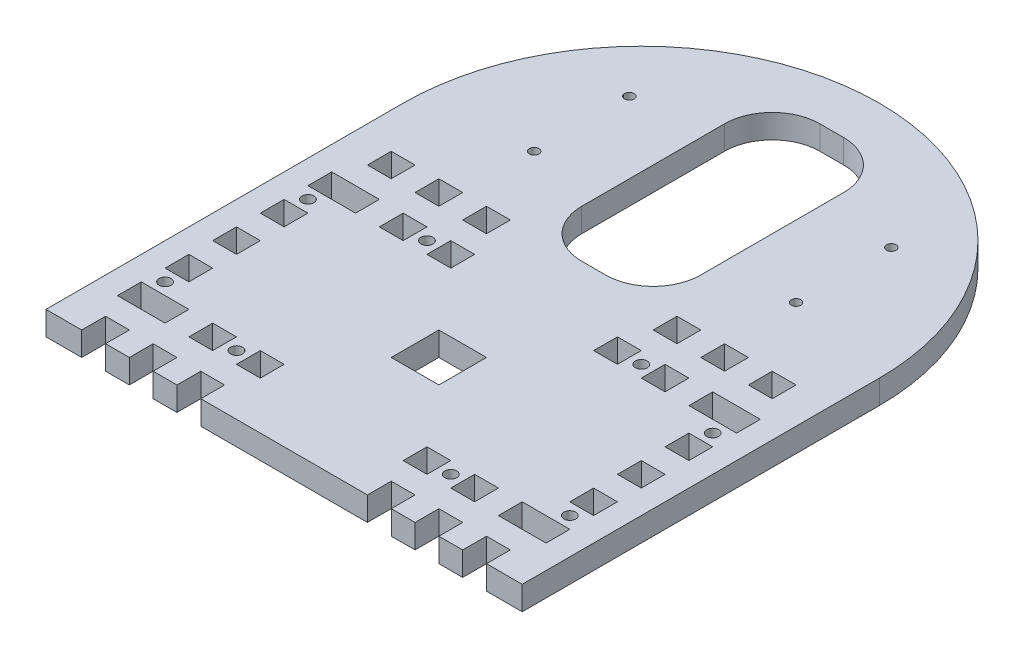
SolidWorks part; units mm, degrees
material "Acrylic (Medium-high impact)"
ref_plane "Front Plane" through (0, 0, 0) normal (0, 0, 1) x (1, 0, 0)
ref_plane "Top Plane" through (0, 0, 0) normal (0, 1, 0) x (1, 0, 0)
ref_plane "Right Plane" through (0, 0, 0) normal (1, 0, 0) x (0, 0, -1)
sketch "Sketch3" plane through (0, 0, 0) normal (0, 1, 0) x (1, 0, 0)
  line L1 (-100, -75) -> (100, -75)
  line L2 (-100, -75) -> (-100, 75)
  line L4 (100, -75) -> (100, 75)
  line L5 (-100, -75) -> (100, 75) construction
  line L6 (-100, 75) -> (100, -75) construction
  arc A0 (-100, 75) -> (100, 75) centre (0, 75) cw
  point P0 (0, 0)
  dimension "D1" = 200
  dimension "D2" = 150
extrude "Boss-Extrude1" add sketch "Sketch3" along normal blind 10
sketch "Sketch2" plane through (0, 10, 0) normal (0, 1, 0) x (1, 0, 0)
  line L1 (-100, -75) -> (100, -75) construction
  line L2 (100, -75) -> (100, 75) construction
  line L7 (30, -45) -> (40, -45)
  line L8 (30, -45) -> (30, -55)
  line L9 (30, -55) -> (40, -55)
  line L10 (40, -45) -> (40, -55)
  line L11 (50, -45) -> (60, -45)
  line L12 (50, -45) -> (50, -55)
  line L13 (50, -55) -> (60, -55)
  line L14 (60, -45) -> (60, -55)
  line L15 (70, -45) -> (90, -45)
  line L16 (70, -45) -> (70, -55)
  line L17 (70, -55) -> (90, -55)
  line L18 (90, -45) -> (90, -55)
  line L19 (90, -35) -> (80, -35)
  line L20 (90, -35) -> (90, -25)
  line L21 (90, -25) -> (80, -25)
  line L22 (80, -35) -> (80, -25)
  line L23 (90, -15) -> (80, -15)
  line L24 (90, -15) -> (90, -5)
  line L25 (90, -5) -> (80, -5)
  line L26 (80, -15) -> (80, -5)
  line L27 (90, 15) -> (80, 15)
  line L28 (90, 15) -> (90, 5)
  line L29 (90, 5) -> (80, 5)
  line L30 (80, 15) -> (80, 5)
  line L31 (90, 35) -> (70, 35)
  line L32 (90, 35) -> (90, 25)
  line L33 (90, 25) -> (70, 25)
  line L34 (70, 35) -> (70, 25)
  line L35 (60, 35) -> (50, 35)
  line L36 (60, 35) -> (60, 25)
  line L37 (60, 25) -> (50, 25)
  line L38 (50, 35) -> (50, 25)
  line L39 (40, 35) -> (30, 35)
  line L40 (40, 35) -> (40, 25)
  line L41 (40, 25) -> (30, 25)
  line L42 (30, 35) -> (30, 25)
  circle A0 centre (45, 30) radius 2.5
  circle A1 centre (45, -50) radius 2.5
  circle A2 centre (85, -40) radius 2.5
  circle A3 centre (85, 20) radius 2.5
  point P0 (0, 0)
  dimension "D3" = 10
  dimension "D19" = 5
  dimension "D23" = 5
  dimension "D2" = 20
  dimension "D4" = 10
  dimension "D5" = 10
  dimension "D6" = 10
  dimension "D7" = 10
  dimension "D8" = 20
  dimension "D9" = 10
  dimension "D10" = 10
  dimension "D11" = 10
  dimension "D12" = 10
  dimension "D13" = 10
  dimension "D14" = 10
  dimension "D15" = 10
  dimension "D16" = 10
  dimension "D17" = 10
  dimension "D18" = 10
  dimension "D20" = 5
  dimension "D21" = 5
  dimension "D22" = 5
  dimension "D24" = 5
  dimension "D25" = 5
extrude "Cut-Extrude1" cut sketch "Sketch2" against normal through all
mirror "Mirror1" about plane through (0, 0, 0) normal (1, 0, 0) of "Cut-Extrude1"
sketch "Sketch4" plane through (0, 10, 0) normal (0, 1, 0) x (1, 0, 0)
  line L0 (100, -75) -> (100, 75) construction
  line L1 (-100, -75) -> (100, -75) construction
  line L2 (-100, 75) -> (-100, -75) construction
  line L4 (-5, 155) -> (5, 155)
  line L5 (-25, 135) -> (-25, 75)
  line L6 (-5, 55) -> (5, 55)
  line L7 (25, 135) -> (25, 75)
  circle A0 centre (55, 125) radius 2
  circle A1 centre (55, 85) radius 2
  circle A2 centre (-55, 125) radius 2
  circle A3 centre (-55, 85) radius 2
  arc A4 (-5, 55) -> (-25, 75) centre (-5, 75) cw
  arc A5 (5, 55) -> (25, 75) centre (5, 75) ccw
  arc A6 (25, 135) -> (5, 155) centre (5, 135) ccw
  arc A7 (-5, 155) -> (-25, 135) centre (-5, 135) ccw
  point P18 (25, 105)
  point P24 (25, 55)
  point P27 (25, 155)
  point P30 (-25, 155)
  dimension "D1" = 4
  dimension "D2" = 4
  dimension "D3" = 4
  dimension "D4" = 4
  dimension "D16" = 20
  dimension "D5" = 110
  dimension "D6" = 110
  dimension "D7" = 40
  dimension "D8" = 40
  dimension "D9" = 45
  dimension "D10" = 160
  dimension "D11" = 45
  dimension "D12" = 50
  dimension "D13" = 100
  dimension "D14" = 25
  dimension "D15" = 20
extrude "Cut-Extrude2" cut sketch "Sketch4" against normal through all
sketch "Sketch5" plane through (0, 10, 0) normal (0, 1, 0) x (1, 0, 0)
  line L0 (100, -75) -> (100, 75) construction
  line L1 (75, 55) -> (85, 55)
  line L2 (75, 55) -> (75, 45)
  line L3 (75, 45) -> (85, 45)
  line L4 (85, 55) -> (85, 45)
  line L5 (55, 55) -> (65, 55)
  line L6 (55, 55) -> (55, 45)
  line L7 (55, 45) -> (65, 45)
  line L8 (65, 55) -> (65, 45)
  line L9 (35, 55) -> (45, 55)
  line L10 (35, 55) -> (35, 45)
  line L11 (35, 45) -> (45, 45)
  line L12 (45, 55) -> (45, 45)
  line L13 (0, -10) -> (111.8569, -10) construction
  line L16 (90, -15) -> (90, -5) construction
  line L17 (0, -20) -> (10, -20)
  line L18 (90, 35) -> (70, 35) construction
  line L20 (0, -20) -> (0, 0)
  line L21 (0, 0) -> (10, 0)
  line L22 (10, -20) -> (10, 0)
  line L23 (45, -75) -> (45, -65)
  line L24 (35, -65) -> (45, -65)
  line L25 (35, -75) -> (35, -65)
  line L26 (35, -75) -> (45, -75)
  line L27 (65, -75) -> (65, -65)
  line L28 (55, -65) -> (65, -65)
  line L29 (55, -75) -> (55, -65)
  line L30 (55, -75) -> (65, -75)
  line L31 (85, -75) -> (85, -65)
  line L32 (75, -65) -> (85, -65)
  line L33 (75, -75) -> (75, -65)
  line L34 (75, -75) -> (85, -75)
  point P16 (90, -10)
  point P27 (5, 0)
  dimension "D2" = 10
  dimension "D3" = 10
  dimension "D4" = 10
  dimension "D5" = 10
  dimension "D6" = 10
  dimension "D7" = 15
  dimension "D8" = 10
  dimension "D9" = 10
  dimension "D10" = 10
  dimension "D11" = 10
extrude "Cut-Extrude3" cut sketch "Sketch5" against normal through all both and the other way through all
mirror "Mirror2" about plane through (0, 0, 0) normal (1, 0, 0) of "Cut-Extrude3"
